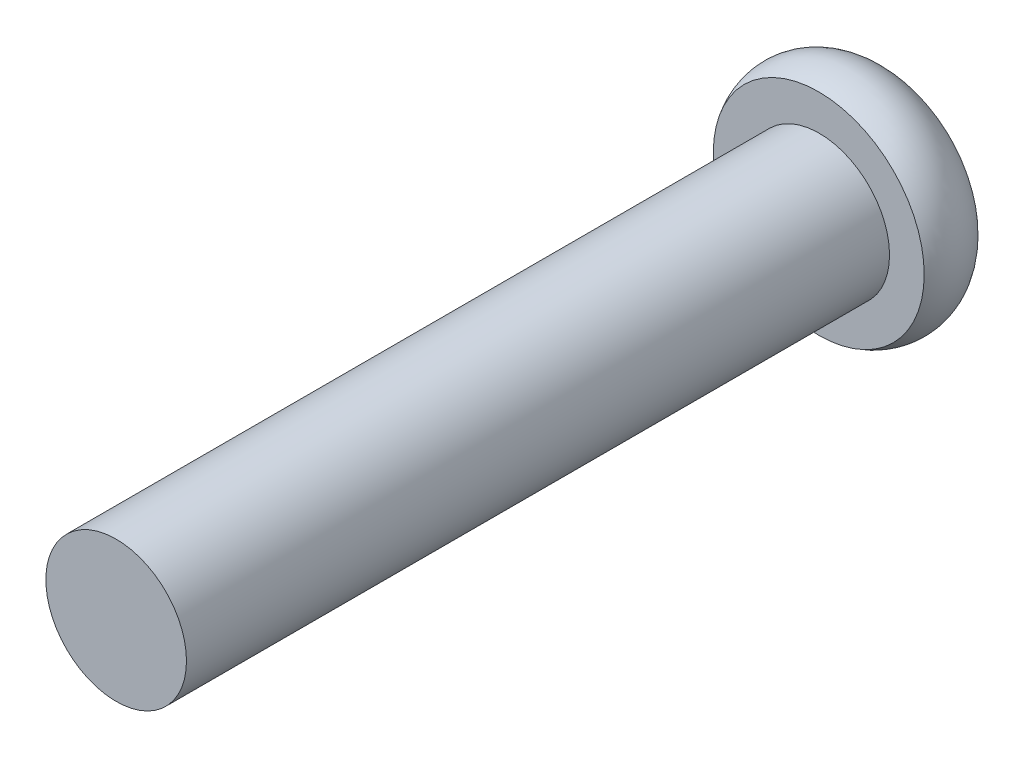
SolidWorks part; units mm, degrees
ref_plane "Front Plane" through (0, 0, 0) normal (0, 0, 1) x (1, 0, 0)
ref_plane "Top Plane" through (0, 0, 0) normal (0, 1, 0) x (1, 0, 0)
ref_plane "Right Plane" through (0, 0, 0) normal (1, 0, 0) x (0, 0, -1)
sketch "Sketch1" plane through (0, 0, 0) normal (0, 1, 0) x (1, 0, 0)
  line L0 (0, 0.6593) -> (0, 4.5218) construction
  line L3 (0, 0) -> (0, 2)
  line L4 (0, 0) -> (3, 0)
  line L5 (0, 2) -> (2.2983, 2)
  arc A0 (2.5735, 1.9174) -> (3, 0) centre (1.7961, 0.7384) cw
  arc A1 (2.5735, 1.9174) -> (2.2983, 2) centre (2.2983, 1.5) ccw
  dimension "D2" = 0.5
revolve "Revolve2" add sketch "Sketch1" angle 360 about L0
sketch "Sketch2" plane through (0, 0, -2) normal (0, 0, -1) x (-1, 0, 0)
  line L0 (0, 0) -> (2.5296, 0) construction
  line L1 (0, 0) -> (0, 1.7464) construction
  line L2 (0.5, -0.5) -> (2, -0.5)
  line L3 (-0.5, 2) -> (0.5, 2)
  line L4 (-0.5, 2) -> (-0.5, 0.5)
  line L5 (-0.5, -2) -> (0.5, -2)
  line L6 (0.5, 2) -> (0.5, 0.5)
  line L7 (0.5, 0.5) -> (2, 0.5)
  line L8 (0.5, -0.5) -> (0.5, -2)
  line L9 (-2, 0.5) -> (-0.5, 0.5)
  line L10 (-2, 0.5) -> (-2, -0.5)
  line L11 (-2, -0.5) -> (-0.5, -0.5)
  line L12 (2, 0.5) -> (2, -0.5)
  line L15 (-0.5, -0.5) -> (-0.5, -2)
  point P4 (0, 0)
  point P12 (0, 0)
  dimension "D1" = 0.5
  dimension "D2" = 2
  dimension "D3" = 2
  dimension "D4" = 2
  dimension "D5" = 0.5
  dimension "D6" = 0.5
  dimension "D7" = 0.5
  dimension "D8" = 0.5
extrude "Cut-Extrude1" cut sketch "Sketch2" against normal blind 2 draft 12
sketch "Sketch3" plane through (0, 0, 0) normal (0, 0, 1) x (1, 0, 0)
  circle A0 centre (0.0136, -0.0136) radius 2
extrude "Boss-Extrude1" add sketch "Sketch3" along normal blind 20
cosmetic thread "Cosmetic Thread2" parameters "D2"=2.439
